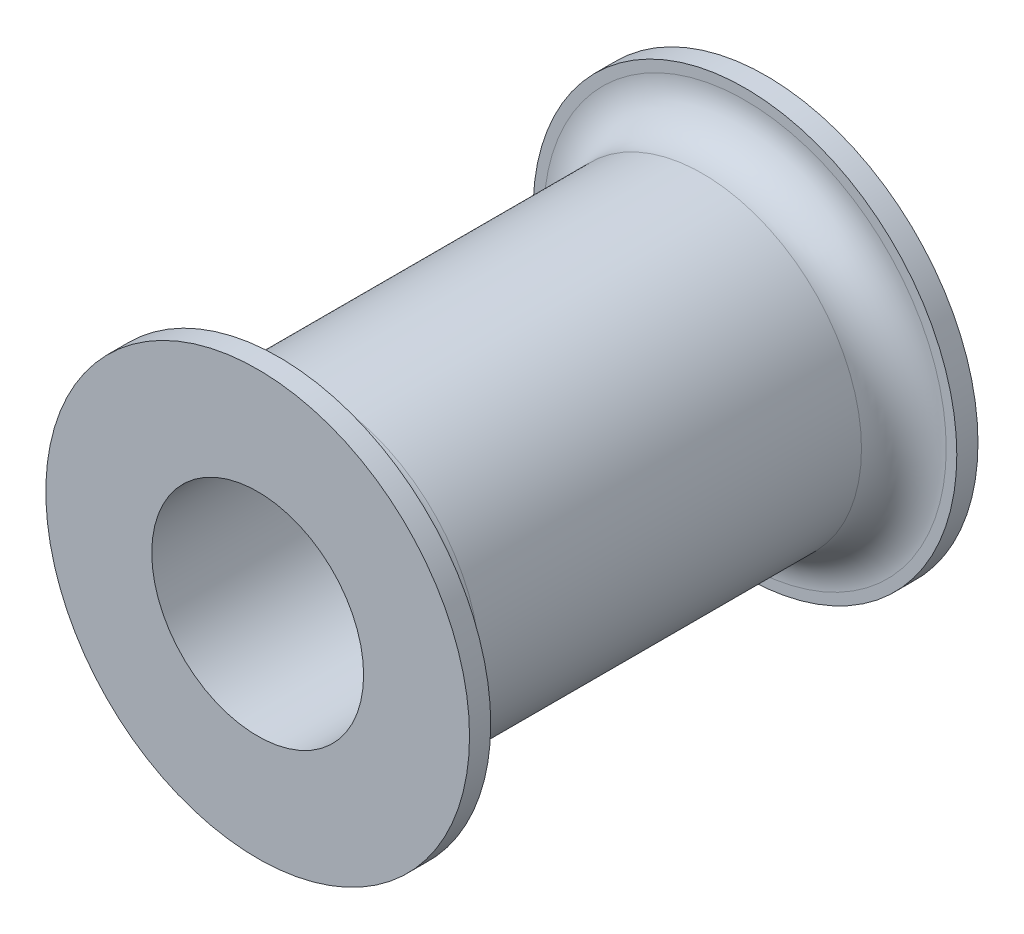
SolidWorks part; units mm, degrees
ref_plane "前视基准面" through (0, 0, 0) normal (0, 0, 1) x (1, 0, 0)
ref_plane "上视基准面" through (0, 0, 0) normal (0, 1, 0) x (1, 0, 0)
ref_plane "右视基准面" through (0, 0, 0) normal (1, 0, 0) x (0, 0, -1)
sketch "草图1" plane through (0, 0, 0) normal (0, 0, 1) x (1, 0, 0)
  circle A0 centre (0, 0) radius 5
  dimension "D1" = 10
extrude "凸台-拉伸1" add sketch "草图1" along normal blind 0.5
sketch "草图2" plane through (0, 0, 0.5) normal (0, 0, 1) x (1, 0, 0)
  circle A0 centre (0, 0) radius 3.75
  dimension "D1" = 7.5
extrude "凸台-拉伸2" add sketch "草图2" along normal blind 11
sketch "草图3" plane through (0, 0, 11.5) normal (0, 0, 1) x (1, 0, 0)
  circle A0 centre (0, 0) radius 5
  dimension "D1" = 10
extrude "凸台-拉伸3" add sketch "草图3" along normal blind 0.5
sketch "草图4" plane through (0, 0, 12) normal (0, 0, 1) x (1, 0, 0)
  circle A0 centre (0, 0) radius 2.5
  dimension "D1" = 5
extrude "切除-拉伸1" cut sketch "草图4" against normal through all
fillet "圆角1" radius 1 2 edges at (3.75, 0, 11.5) (3.75, 0, 0.5)
